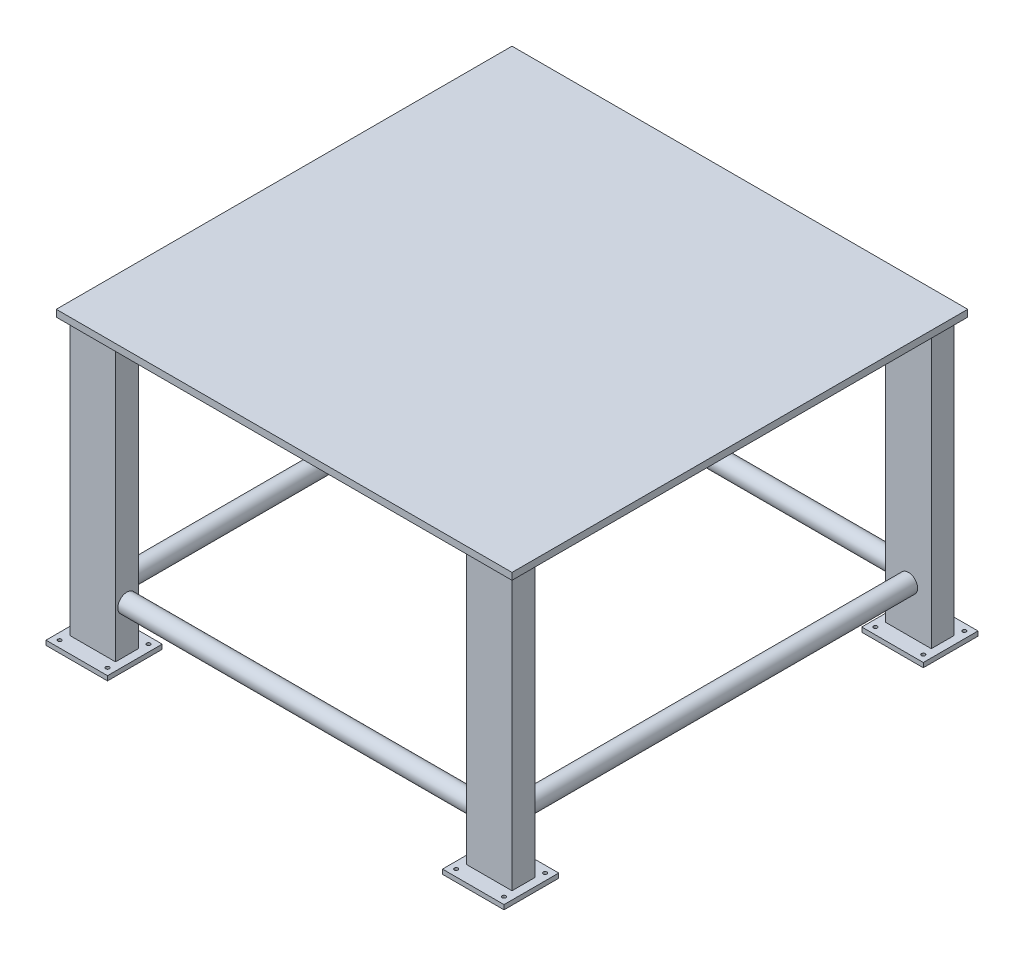
SolidWorks part; units mm, degrees
ref_plane "Front Plane" through (0, 0, 0) normal (0, 0, 1) x (1, 0, 0)
ref_plane "Top Plane" through (0, 0, 0) normal (0, 1, 0) x (1, 0, 0)
ref_plane "Right Plane" through (0, 0, 0) normal (1, 0, 0) x (0, 0, -1)
sketch "Sketch1" plane through (0, 0, 0) normal (0, 1, 0) x (1, 0, 0)
  line L1 (-500, 500) -> (500, 500)
  line L2 (-500, 500) -> (-500, -500)
  line L3 (-500, -500) -> (500, -500)
  line L4 (500, 500) -> (500, -500)
  line L5 (-500, 500) -> (500, -500) construction
  line L6 (-500, -500) -> (500, 500) construction
  point P0 (0, 0)
  dimension "D1" = 1000
extrude "Boss-Extrude1" add sketch "Sketch1" along normal blind 15
sketch "Sketch2" plane through (0, 0, 0) normal (0, -1, 0) x (1, 0, 0)
  line L0 (-500, 500) -> (500, 500) construction
  line L1 (385, 485) -> (485, 485)
  line L2 (385, 485) -> (385, 435)
  line L3 (385, 435) -> (485, 435)
  line L4 (485, 485) -> (485, 435)
  line L5 (500, 500) -> (500, -500) construction
  dimension "D1" = 100
  dimension "D2" = 50
  dimension "D3" = 15
  dimension "D4" = 15
extrude "Boss-Extrude2" add sketch "Sketch2" along normal blind 605
sketch "Sketch3" plane through (0, -605, 0) normal (0, -1, 0) x (1, 0, 0)
  line L1 (367.5, 520) -> (502.5, 520)
  line L2 (367.5, 520) -> (367.5, 400)
  line L3 (367.5, 400) -> (502.5, 400)
  line L4 (502.5, 520) -> (502.5, 400)
  line L5 (367.5, 520) -> (502.5, 400) construction
  line L6 (367.5, 400) -> (502.5, 520) construction
  line L8 (385, 435) -> (485, 435) construction
  line L9 (385, 485) -> (385, 435) construction
  point P0 (435, 460)
  point P9 (385, 460)
  dimension "D1" = 135
  dimension "D2" = 120
  dimension "D3" = 25
  dimension "D4" = 50
extrude "Boss-Extrude3" add sketch "Sketch3" along normal blind 10
sketch "Sketch5" plane through (0, -615, 0) normal (0, -1, 0) x (1, 0, 0)
  line L0 (367.5, 520) -> (367.5, 400) construction
  line L1 (502.5, 520) -> (367.5, 520) construction
  line L2 (367.5, 400) -> (502.5, 400) construction
  line L3 (502.5, 400) -> (502.5, 520) construction
  circle A0 centre (382.5, 505) radius 4
  circle A1 centre (382.5, 415) radius 4
  circle A2 centre (487.5, 415) radius 4
  circle A3 centre (487.5, 505) radius 4
  point P8 (0, 0)
  point P9 (0, 0)
  point P10 (0, 0)
  point P11 (0, 0)
  dimension "D1" = 8
  dimension "D2" = 15
  dimension "D3" = 15
  dimension "D4" = 15
  dimension "D5" = 15
extrude "Cut-Extrude1" cut sketch "Sketch5" against normal up to surface (10 mm away) up to face at (435, -605, 460)
mirror "Mirror1" about plane through (0, 0, 0) normal (0, 0, 1) of "Cut-Extrude1", "Boss-Extrude3", "Boss-Extrude2"
mirror "Mirror2" about plane through (0, 0, 0) normal (1, 0, 0) of "Mirror1", "Cut-Extrude1", "Boss-Extrude3", "Boss-Extrude2"
sketch "Sketch6" plane through (0, 0, 435) normal (0, 0, -1) x (-1, 0, 0)
  line L0 (-385, -605) -> (-485, -605) construction
  line L1 (-485, -605) -> (-485, 0) construction
  circle A0 centre (-435, -505) radius 20
  dimension "D1" = 100
  dimension "D2" = 40
  dimension "D3" = 50
extrude "Boss-Extrude4" add sketch "Sketch6" along normal up to surface (870 mm away) up to face at (435, -302.5, -435)
sketch "Sketch7" plane through (385, 0, 0) normal (-1, 0, 0) x (0, 0, 1)
  line L0 (485, -605) -> (435, -605) construction
  line L1 (485, -605) -> (485, 0) construction
  circle A0 centre (460, -505) radius 20
  dimension "D1" = 40
  dimension "D2" = 100
  dimension "D3" = 25
extrude "Boss-Extrude5" add sketch "Sketch7" along normal up to surface (770 mm away) up to face at (-385, -302.5, 460)
mirror "Mirror3" about plane through (0, 0, 0) normal (0, 0, 1) of "Boss-Extrude5"
mirror "Mirror4" about plane through (0, 0, 0) normal (1, 0, 0) of "Boss-Extrude4"
